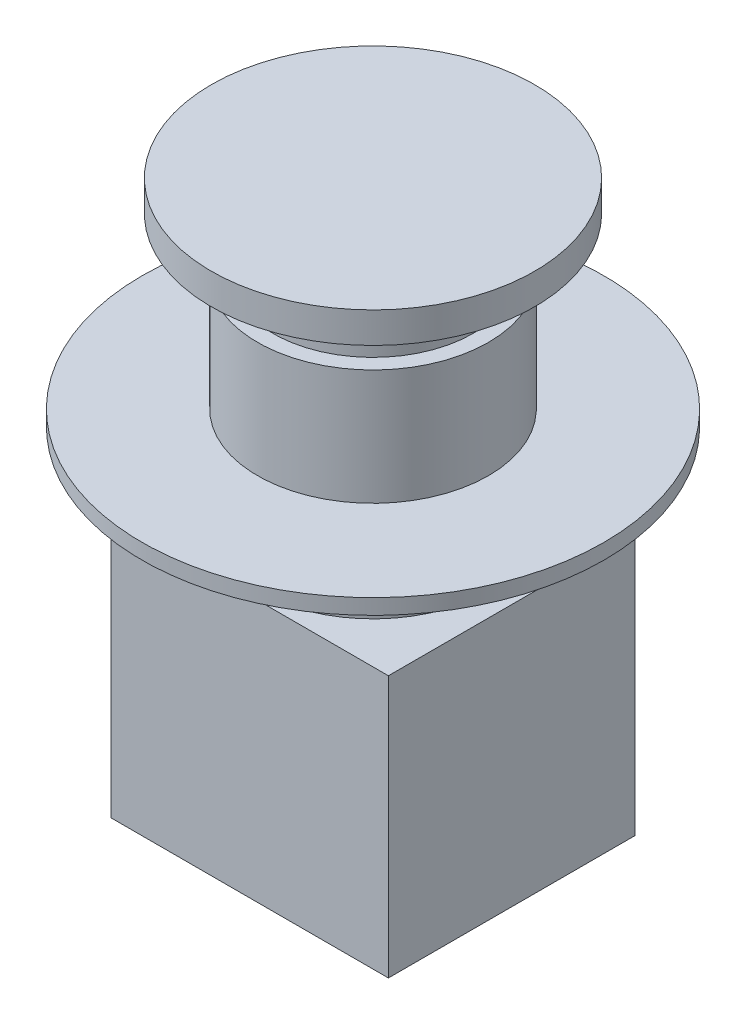
SolidWorks part; units mm, degrees
ref_plane "Front Plane" through (0, 0, 0) normal (0, 0, 1) x (1, 0, 0)
ref_plane "Top Plane" through (0, 0, 0) normal (0, 1, 0) x (1, 0, 0)
ref_plane "Right Plane" through (0, 0, 0) normal (1, 0, 0) x (0, 0, -1)
sketch "Esquisse1" plane through (0, 0, 0) normal (0, 0, 1) x (1, 0, 0)
  line L0 (0, 0) -> (30, 0)
  line L1 (30, 0) -> (30, 2)
  line L2 (30, 2) -> (15, 2)
  line L3 (15, 2) -> (15, 17)
  line L4 (15, 17) -> (13, 17)
  line L5 (13, 17) -> (13, 24)
  line L6 (13, 24) -> (21, 24)
  line L7 (21, 24) -> (21, 28)
  line L8 (21, 28) -> (0, 28)
  line L9 (0, 28) -> (0, 0)
  dimension "D1" = 28
  dimension "D2" = 30
  dimension "D3" = 2
  dimension "D4" = 15
  dimension "D5" = 15
  dimension "D6" = 2
  dimension "D7" = 7
  dimension "D8" = 8
revolve "Révolution1" add sketch "Esquisse1" angle 360 about L9
ref_plane "Plan1" through (0, 0, 0) normal (0, -1, 0) x (-1, 0, 0)
sketch "Esquisse2" plane through (0, 0, 0) normal (0, -1, 0) x (-1, 0, 0)
  circle A0 centre (0, 0) radius 15
  dimension "D1" = 30
extrude "Boss.-Extru.1" add sketch "Esquisse2" along normal blind 11
ref_plane "Plan2" through (0, -11, 0) normal (0, -1, 0) x (-1, 0, 0)
sketch "Esquisse3" plane through (0, -11, 0) normal (0, -1, 0) x (-1, 0, 0)
  line L1 (18, 16) -> (-18, 16)
  line L2 (18, 16) -> (18, -16)
  line L3 (18, -16) -> (-18, -16)
  line L4 (-18, 16) -> (-18, -16)
  line L5 (18, 16) -> (-18, -16) construction
  line L6 (18, -16) -> (-18, 16) construction
  circle A1 centre (0, 0) radius 15 construction
  point P0 (0, 0)
  dimension "D1" = 16
  dimension "D2" = 36
extrude "Boss.-Extru.2" add sketch "Esquisse3" along normal blind 34
